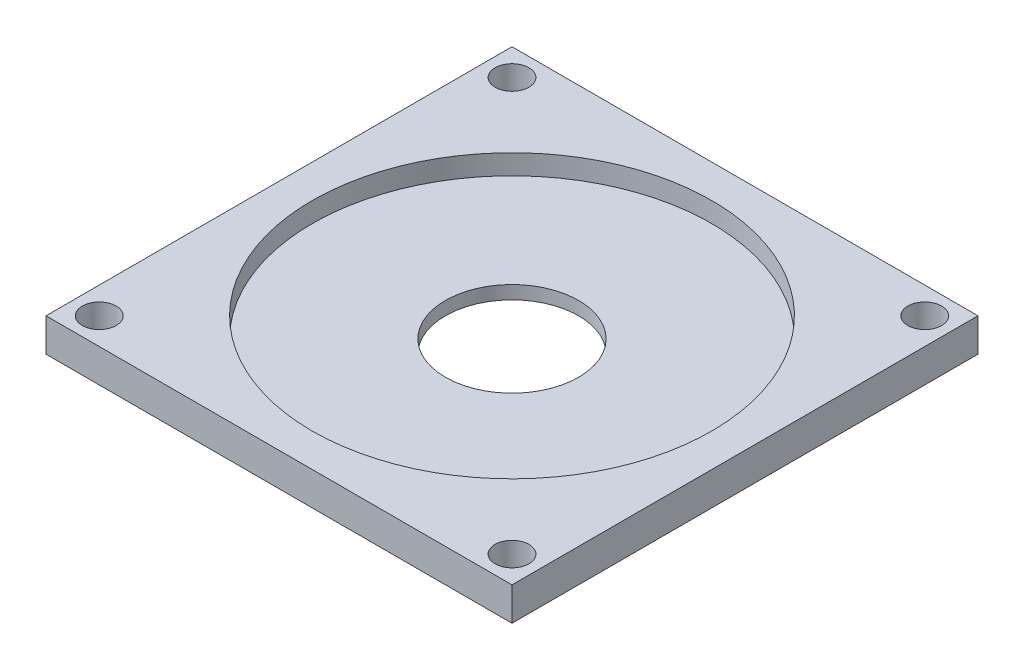
SolidWorks part; units mm, degrees
ref_plane "Alzado" through (0, 0, 0) normal (0, 0, 1) x (1, 0, 0)
ref_plane "Planta" through (0, 0, 0) normal (0, 1, 0) x (1, 0, 0)
ref_plane "Vista lateral" through (0, 0, 0) normal (1, 0, 0) x (0, 0, -1)
sketch "Croquis2" plane through (0, 0, 0) normal (0, 1, 0) x (1, 0, 0)
  line L1 (0, 0) -> (700, 0)
  line L2 (0, 0) -> (0, 700)
  line L3 (0, 700) -> (700, 700)
  line L4 (700, 0) -> (700, 700)
  dimension "D1" = 700
  dimension "D2" = 700
extrude "Saliente-Extruir1" add sketch "Croquis2" along normal blind 50
sketch "Croquis3" plane through (0, 50, 0) normal (0, 1, 0) x (1, 0, 0)
  line L0 (700, 700) -> (0, 700) construction
  line L1 (0, 700) -> (0, 0) construction
  line L2 (700, 0) -> (700, 700) construction
  line L3 (0, 0) -> (700, 0) construction
  circle A0 centre (40, 40) radius 25.4
  circle A1 centre (660, 40) radius 25.4
  circle A2 centre (660, 660) radius 25.4
  circle A3 centre (40, 660) radius 25.4
  dimension "D1" = 50.8
  dimension "D2" = 50.8
  dimension "D3" = 50.8
  dimension "D4" = 50.8
  dimension "D5" = 40
  dimension "D6" = 40
  dimension "D7" = 40
  dimension "D8" = 40
  dimension "D9" = 40
  dimension "D10" = 40
  dimension "D11" = 40
  dimension "D12" = 40
extrude "Cortar-Extruir1" cut sketch "Croquis3" against normal through all both and the other way through all
sketch "Croquis4" plane through (0, 50, 0) normal (0, 1, 0) x (1, 0, 0)
  line L5 (0, 700) -> (0, 0) construction
  line L6 (0, 0) -> (700, 0) construction
  circle A0 centre (350, 350) radius 300
  dimension "D5" = 600
  dimension "D1" = 350
  dimension "D2" = 350
extrude "Cortar-Extruir4" cut sketch "Croquis4" against normal blind 30
sketch "Croquis5" plane through (0, 20, 0) normal (0, 1, 0) x (1, 0, 0)
  line L0 (0, 700) -> (0, 0) construction
  line L2 (0, 0) -> (700, 0) construction
  circle A0 centre (350, 350) radius 100
  dimension "D1" = 200
  dimension "D2" = 350
  dimension "D3" = 350
extrude "Cortar-Extruir5" cut sketch "Croquis5" against normal blind 20
